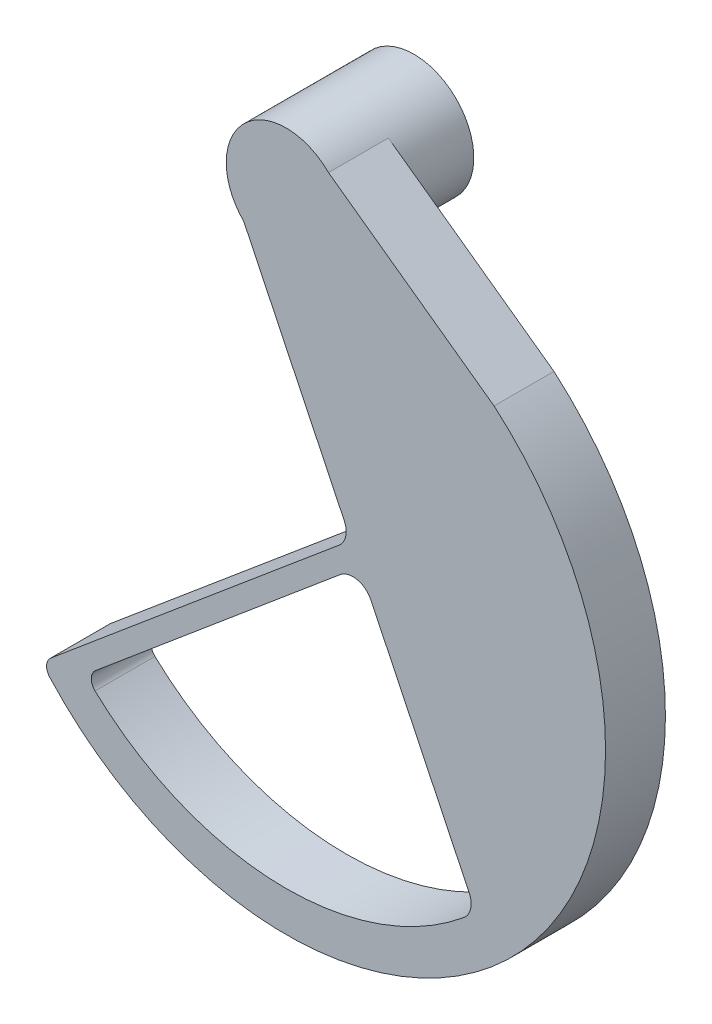
SolidWorks part; units mm, degrees
ref_plane "正面" through (0, 0, 0) normal (0, 0, 1) x (1, 0, 0)
ref_plane "平面" through (0, 0, 0) normal (0, 1, 0) x (1, 0, 0)
ref_plane "右側面" through (0, 0, 0) normal (1, 0, 0) x (0, 0, -1)
sketch "ｽｹｯﾁ4" plane through (0, 0, 0) normal (0, 0, 1) x (1, 0, 0)
  line L0 (0, 0.7897) -> (0, 0)
  line L1 (-53.6231, -124.9951) -> (-58.9406, -129.4571)
  line L3 (-10.6066, -10.6066) -> (14.5363, -62.8896)
  line L4 (-53.6231, -124.9951) -> (13.2442, -68.8868)
  line L5 (21.2324, -76.8138) -> (45.8448, -127.9938)
  line L6 (10.6066, 10.6066) -> (52.0762, -19.2705)
  line L7 (-58.0696, -135.2532) -> (-57.9498, -135.1527)
  line L8 (-47.7477, -126.5866) -> (13.5112, -75.1515)
  arc A1 (-59.2335, -133.7716) -> (52.0762, -19.2705) centre (0, -80) ccw
  arc A2 (-47.8702, -131.073) -> (44.5187, -134.0193) centre (0, -80) ccw
  arc A3 (10.6066, 10.6066) -> (-10.6066, -10.6066) centre (0, 0) ccw
  arc A4 (-59.2335, -133.7716) -> (-58.9406, -129.4571) centre (-57.0123, -131.7552) cw
  arc A5 (-47.8702, -131.073) -> (-47.7477, -126.5866) centre (-45.8186, -128.8841) cw
  arc A6 (13.5112, -75.1515) -> (21.2324, -76.8138) centre (16.7264, -78.9807) cw
  arc A7 (13.2442, -68.8868) -> (14.5363, -62.8896) centre (10.0302, -65.0566) ccw
  arc A8 (45.8448, -127.9938) -> (44.5187, -134.0193) centre (41.3388, -130.1608) cw
  point P18 (-61.2836, -131.423)
  point P21 (-50.2744, -128.7081)
  point P24 (18.4421, -71.0114)
  dimension "D3" = 140
  dimension "D4" = 30
  dimension "D5" = 5
  dimension "D6" = 3
  dimension "D7" = 3
  dimension "D8" = 5
  dimension "D9" = 5
  dimension "D10" = 5
  dimension "D2" = 5
extrude "ﾎﾞｽ - 押し出し1" add sketch "ｽｹｯﾁ4" along normal blind 15
sketch "ｽｹｯﾁ9" plane through (0, 0, 0) normal (0, 0, -1) x (-1, 0, 0)
  circle A0 centre (0, 0) radius 15
  dimension "D1" = 30
extrude "ﾎﾞｽ - 押し出し3" add sketch "ｽｹｯﾁ9" along normal blind 17
sketch "ｽｹｯﾁ10" plane through (0, 0, -17) normal (0, 0, -1) x (-1, 0, 0)
  circle A0 centre (0, 0) radius 10.1
extrude "ｶｯﾄ - 押し出し4" cut sketch "ｽｹｯﾁ10" against normal blind 2
